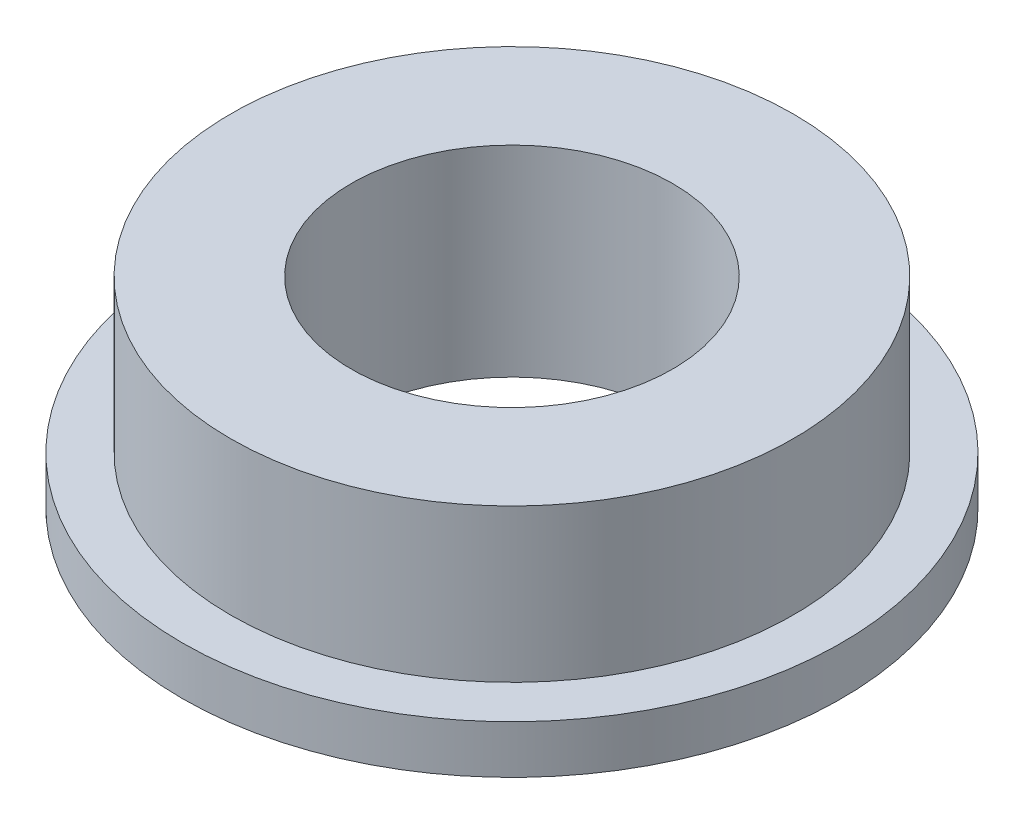
SolidWorks part; units mm, degrees
ref_plane "前视基准面" through (0, 0, 0) normal (0, 0, 1) x (1, 0, 0)
ref_plane "上视基准面" through (0, 0, 0) normal (0, 1, 0) x (1, 0, 0)
ref_plane "右视基准面" through (0, 0, 0) normal (1, 0, 0) x (0, 0, -1)
sketch "草图1" plane through (0, 0, 0) normal (0, 1, 0) x (1, 0, 0)
  circle A0 centre (0, 0) radius 4.1
  dimension "D1" = 8.2
extrude "凸台-拉伸1" add sketch "草图1" along normal blind 0.6
sketch "草图2" plane through (0, 0.6, 0) normal (0, 1, 0) x (1, 0, 0)
  circle A0 centre (0, 0) radius 3.5
  dimension "D1" = 7
extrude "凸台-拉伸2" add sketch "草图2" along normal blind 1.9
hole_wizard "孔1" positions "草图3" profile "草图4" legacy end condition through all
sketch "草图3" plane through (0, 0, 0) normal (0, -1, 0) x (-1, 0, 0)
  point P0 (0, 0)
sketch "草图4" plane through (0, 0, 0) normal (1, 0, 0) x (0, 0, -1)
  line L0 (0, 0) -> (0, 2.5)
  line L1 (0, 2.5) -> (2, 2.5)
  line L2 (2, 2.5) -> (2, 0)
  line L3 (2, 0) -> (0, 0)
  line L4 (0, 110) -> (0, -10) construction
  dimension "直径" = 4
  dimension "深度" = 2.5
